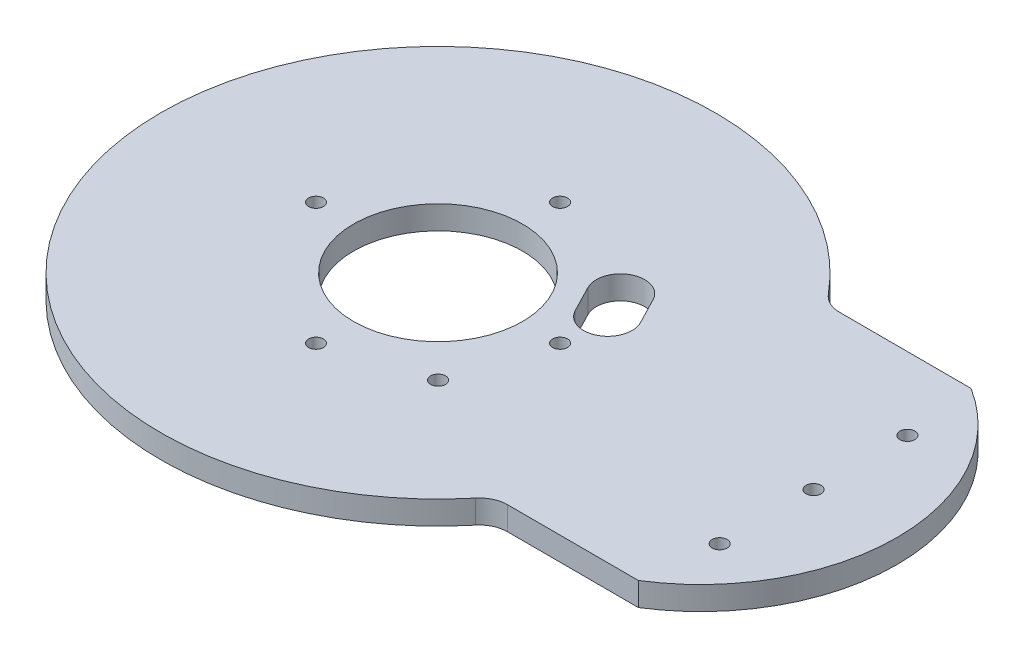
SolidWorks part; units mm, degrees
ref_plane "Front" through (0, 0, 0) normal (0, 0, 1) x (1, 0, 0)
ref_plane "Top" through (0, 0, 0) normal (0, 1, 0) x (1, 0, 0)
ref_plane "Right" through (0, 0, 0) normal (1, 0, 0) x (0, 0, -1)
sketch "Sketch1" plane through (0, 0, 0) normal (0, 1, 0) x (1, 0, 0)
  line L0 (26.6, 0) -> (-75, 0) construction
  line L1 (24.1992, -45) -> (-14.9507, -44.9361)
  line L2 (24.1992, 45) -> (-15.0466, 45.064)
  arc A0 (24.1992, -45) -> (24.1992, 45) centre (26.6, 0) ccw
  circle A2 centre (-75, 0) radius 22.098 construction
  circle A3 centre (26.6, 0) radius 2.0193
  arc A4 (-15.0466, 45.064) -> (-14.9507, -44.9361) centre (-75, 0) ccw
  point P3 (0, 0)
  dimension "D1" = 101.6
  dimension "D3" = 44.196
  dimension "D4" = 4.0386
  dimension "D5" = 75.0011
  dimension "D2" = 45.064
extrude "Boss-Extrude1" add sketch "Sketch1" along normal blind 6.35
hole_wizard "M3x0.5 Tapped Hole1" [suppressed] positions "Sketch5" profile "Sketch4" tap size "M3x0.5" standard "ANSI Metric"
sketch "Sketch5" plane through (0, 6.35, 0) normal (0, 1, 0) x (1, 0, 0)
  circle A0 centre (-75, 0) radius 27
  point P0 (-75, -27)
  point P3 (-102, 0)
  point P6 (-75, 27)
  point P9 (-48, 0)
  dimension "D1" = 54
sketch "Sketch4" plane through (-75, 6.35, 27) normal (1, 0, 0) x (0, 0, 1)
  line L0 (0, 0) -> (0, 6.35)
  line L1 (0, 6.35) -> (1.25, 6.35)
  line L2 (1.25, 6.35) -> (1.25, 0)
  line L5 (1.25, 0) -> (0, 0)
  line L11 (0, -6.35) -> (0, 107.95) construction
  dimension "Thru Tap Drill Dia." = 2.5
  dimension "Thru Tap Drill Depth" = 6.35
cosmetic thread "Hole Thread1" [suppressed] parameters "D2"=3
cosmetic thread "Hole Thread2" [suppressed] parameters "D2"=3
cosmetic thread "Hole Thread3" [suppressed] parameters "D2"=3
cosmetic thread "Hole Thread4" [suppressed] parameters "D2"=3
hole_wizard "M3 Clearance Slot1" [suppressed] positions "Sketch11" profile "Sketch10" size "M3" standard "ANSI Metric"
sketch "Sketch11" plane through (0, 6.35, 0) normal (0, 1, 0) x (1, 0, 0)
  line L0 (-50, -30) -> (-20, -30) construction
  line L1 (-75, 0) -> (75, 0) construction
  circle A0 centre (-75, 0) radius 22.098 construction
  point P0 (-35, -30)
  dimension "D1" = 30
  dimension "D2" = 40
  dimension "D3" = 30
sketch "Sketch10" plane through (-35, 6.35, 30) normal (1, 0, 0) x (0, 0, 1)
  line L0 (0, 0) -> (0, 26.4215)
  line L1 (0, 26.4215) -> (1.7, 25.4)
  line L2 (1.7, 25.4) -> (1.7, 0)
  line L5 (1.7, 0) -> (0, 0)
  line L10 (0, 26.4215) -> (-1.7, 25.4) construction
  line L11 (0, -6.35) -> (0, 107.95) construction
  dimension "Hole Dia." = 3.4
  dimension "Hole Depth" = 25.4
  dimension "Drill Angle" = 118
hole_wizard "M3x0.5 Tapped Hole3" [suppressed] positions "Sketch13" profile "Sketch14" tap size "M3x0.5" standard "ANSI Metric"
sketch "Sketch13" plane through (0, 0, 0) normal (0, -1, 0) x (-1, 0, 0)
  point P0 (21.7, 30)
sketch "Sketch14" plane through (-21.7, 0, -30) normal (1, 0, 0) x (0, 0, -1)
  line L0 (0, 0) -> (0, 6.35)
  line L1 (0, 6.35) -> (1.25, 6.35)
  line L2 (1.25, 6.35) -> (1.25, 0)
  line L5 (1.25, 0) -> (0, 0)
  line L11 (0, -6.35) -> (0, 107.95) construction
  dimension "Thru Tap Drill Dia." = 2.5
  dimension "Thru Tap Drill Depth" = 6.35
cosmetic thread "Hole Thread7" [suppressed] parameters "D2"=3
extrude "Cut-Extrude1" cut sketch "Sketch16" against normal blind 6.35
sketch "Sketch16" plane through (0.9648, 6.35, 105.9343) normal (0, 1, 0) x (-1, 0, 0)
  circle A6 centre (75.9648, -105.9343) radius 22.86
  circle A7 centre (50.801, -80.7705) radius 2.0193
  circle A8 centre (42.9448, -105.9343) radius 2.0193
  circle A9 centre (75.9648, -72.9143) radius 2.0193
  circle A10 centre (108.9848, -105.9343) radius 2.0193
  circle A11 centre (75.9648, -138.9543) radius 2.0193
fillet "Fillet1" radius 7.62 2 edges at (-14.9507, 3.175, 44.9361) (-15.0466, 3.175, -45.064)
hole_wizard "#21 (0.159) Diameter Hole1" positions "Sketch17" profile "Sketch18" hole size "#21" standard "ANSI Inch" end condition through all
sketch "Sketch17" plane through (0, 6.35, 0) normal (0, 1, 0) x (1, 0, 0)
  line L0 (26.6, -25.4) -> (26.6, 25.4) construction
  circle A3 centre (26.6, 0) radius 2.0193 construction
  circle A4 centre (26.6, 0) radius 2.0193 construction
  point P0 (26.6, 25.4)
  point P2 (26.6, -25.4)
  point P24 (26.6, 0)
  dimension "D1" = 50.8
sketch "Sketch18" plane through (26.6, 6.35, -25.4) normal (1, 0, 0) x (0, 0, 1)
  line L0 (0, 0) -> (0, 6.35)
  line L1 (0, 6.35) -> (2.0193, 6.35)
  line L2 (2.0193, 6.35) -> (2.0193, 0)
  line L5 (2.0193, 0) -> (0, 0)
  line L11 (0, -6.35) -> (0, 107.95) construction
  dimension "Thru Hole Dia." = 4.0386
  dimension "Thru Hole Depth" = 6.35
sketch "Sketch19" plane through (0, 6.35, 0) normal (0, 1, 0) x (1, 0, 0)
  line L0 (26.6, 0) -> (71.664, 0) construction
  arc A0 (24.1992, 45) -> (24.1992, -45) centre (-3.9435, 0) cw
  arc A1 (24.1992, -45) -> (24.1992, 45) centre (26.6, 0) ccw construction
  arc A2 (24.1992, 45) -> (24.1992, -45) centre (26.6, 0) cw
  point P11 (49.132, 0)
extrude "Cut-Extrude2" cut sketch "Sketch19" against normal through all
sketch "Sketch20" plane through (0, 6.35, 0) normal (0, 1, 0) x (1, 0, 0)
  line L0 (-45.4314, 19.8023) -> (-41.7582, 12.705) construction
  line L1 (-39.6125, 22.8138) -> (-35.9394, 15.7166)
  line L2 (-51.2502, 16.7907) -> (-47.5771, 9.6935)
  arc A0 (-39.6125, 22.8138) -> (-51.2502, 16.7907) centre (-45.4314, 19.8023) ccw
  arc A1 (-47.5771, 9.6935) -> (-35.9394, 15.7166) centre (-41.7582, 12.705) ccw
  circle A2 centre (-75, 0) radius 22.86 construction
  circle A3 centre (-41.98, 0) radius 2.0193 construction
  point P2 (-43.5948, 16.2537)
  dimension "D4" = 6.552
  dimension "D5" = 7.9914
  dimension "D1" = 35.587
  dimension "D2" = 35.587
  dimension "D3" = 12.705
extrude "Cut-Extrude3" cut sketch "Sketch20" against normal through all
